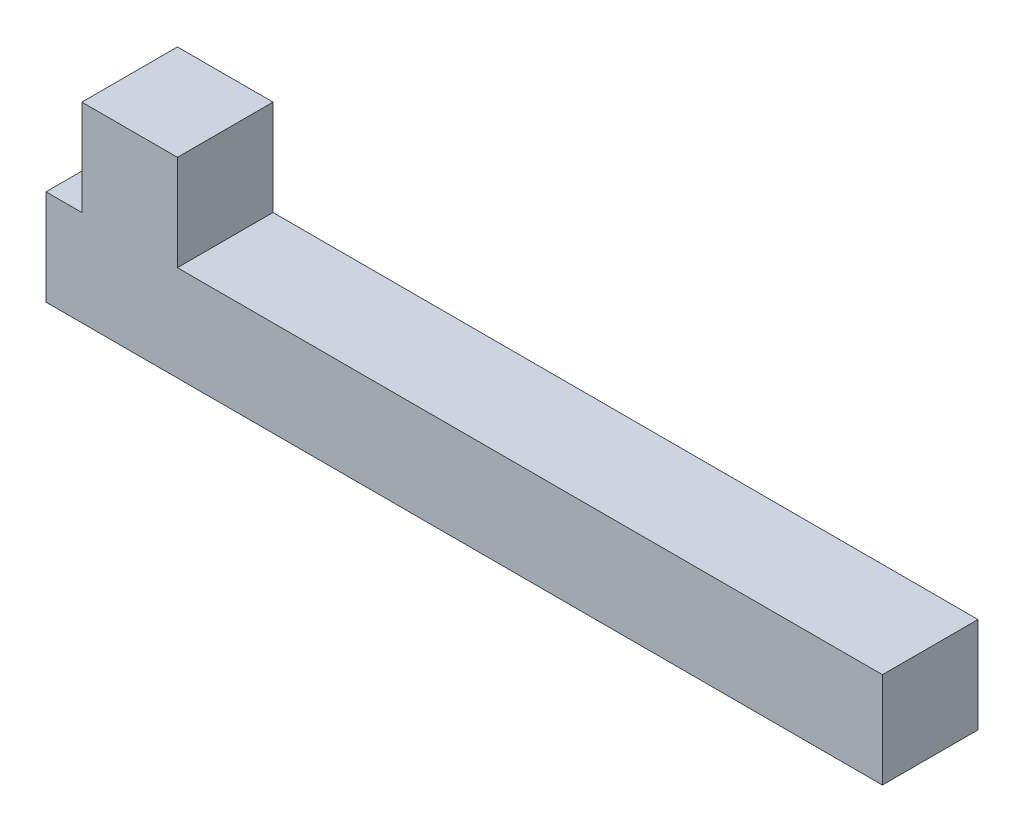
SolidWorks part; units mm, degrees
ref_plane "Plan de face" through (0, 0, 0) normal (0, 0, 1) x (1, 0, 0)
ref_plane "Plan de dessus" through (0, 0, 0) normal (0, 1, 0) x (1, 0, 0)
ref_plane "Plan de droite" through (0, 0, 0) normal (1, 0, 0) x (0, 0, -1)
sketch "Esquisse1" plane through (0, 0, 0) normal (0, 0, 1) x (1, 0, 0)
  line L0 (0, 0) -> (0, 4)
  line L1 (0, 4) -> (1.5, 4)
  line L2 (1.5, 4) -> (1.5, 8)
  line L3 (1.5, 8) -> (5.5, 8)
  line L4 (5.5, 8) -> (5.5, 4)
  line L5 (5.5, 4) -> (35, 4)
  line L6 (35, 4) -> (35, 0)
  line L7 (35, 0) -> (0, 0)
  dimension "D1" = 4
  dimension "D2" = 1.5
  dimension "D3" = 35
extrude "Boss.-Extru.1" add sketch "Esquisse1" along normal blind 4
